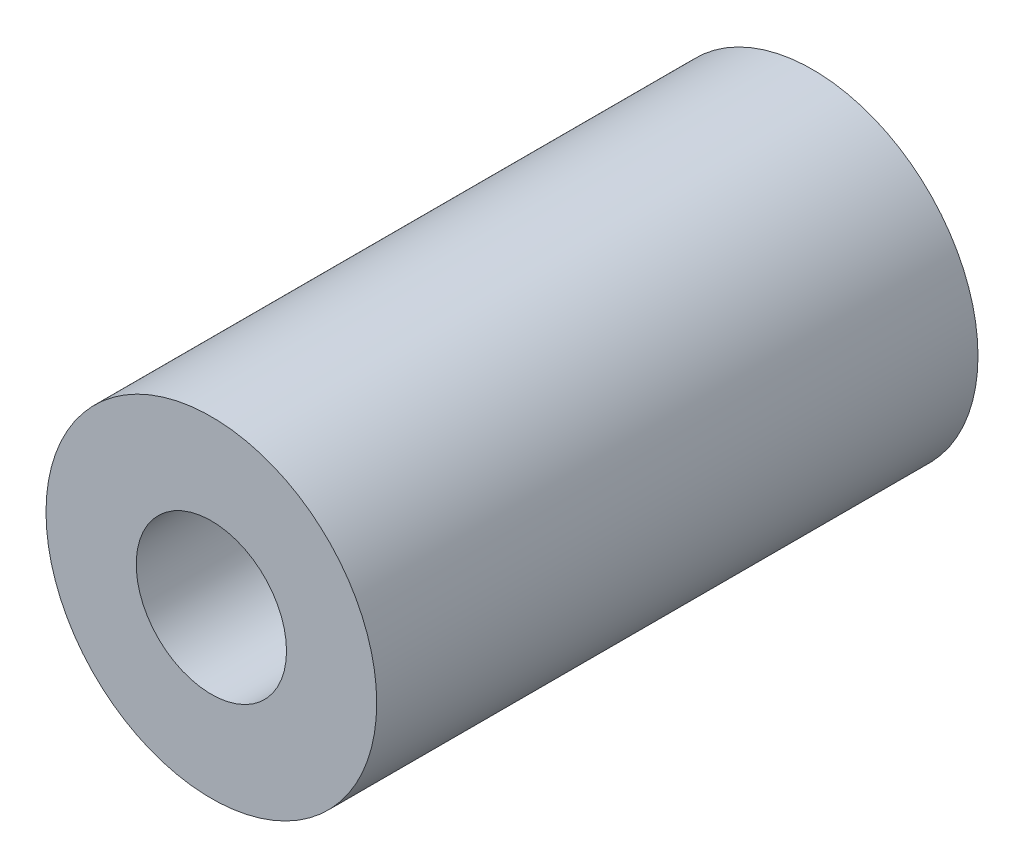
SolidWorks part; units mm, degrees
material "Plain Carbon Steel"
ref_plane "Front Plane" through (0, 0, 0) normal (0, 0, 1) x (1, 0, 0)
ref_plane "Top Plane" through (0, 0, 0) normal (0, 1, 0) x (1, 0, 0)
ref_plane "Right Plane" through (0, 0, 0) normal (1, 0, 0) x (0, 0, -1)
sketch "Sketch1" plane through (0, 0, 0) normal (0, 0, 1) x (1, 0, 0)
  circle A0 centre (0, 0) radius 22
  circle A1 centre (0, 0) radius 10
  dimension "D1" = 44
  dimension "D2" = 20
extrude "Boss-Extrude1" add sketch "Sketch1" along normal blind 80
